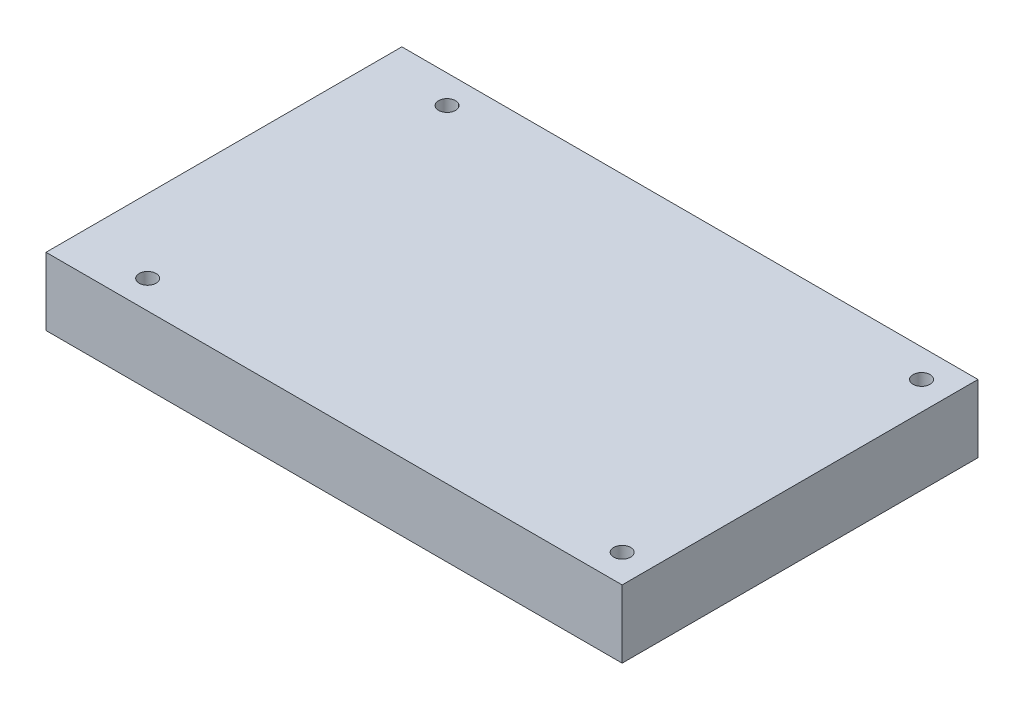
SolidWorks part; units mm, degrees
ref_plane "Front Plane" through (0, 0, 0) normal (0, 0, 1) x (1, 0, 0)
ref_plane "Top Plane" through (0, 0, 0) normal (0, 1, 0) x (1, 0, 0)
ref_plane "Right Plane" through (0, 0, 0) normal (1, 0, 0) x (0, 0, -1)
sketch "Sketch1" plane through (0, 0, 0) normal (0, 1, 0) x (1, 0, 0)
  line L1 (51, -31.5) -> (-51, -31.5)
  line L2 (51, -31.5) -> (51, 31.5)
  line L3 (51, 31.5) -> (-51, 31.5)
  line L4 (-51, -31.5) -> (-51, 31.5)
  line L5 (51, -31.5) -> (-51, 31.5) construction
  line L6 (51, 31.5) -> (-51, -31.5) construction
  point P0 (0, 0)
  dimension "D1" = 102
  dimension "D2" = 63
extrude "Boss-Extrude1" add sketch "Sketch1" along normal blind 12
sketch "Sketch2" plane through (0, 12, 0) normal (0, 1, 0) x (1, 0, 0)
  line L0 (-51, 31.5) -> (-51, -31.5) construction
  line L1 (51, 31.5) -> (-51, 31.5) construction
  circle A0 centre (-38, 26.5) radius 1.5
  circle A1 centre (46, 26.5) radius 1.5
  circle A2 centre (46, -26.5) radius 1.5
  circle A3 centre (-38, -26.5) radius 1.5
  dimension "D1" = 3
  dimension "D2" = 13
  dimension "D3" = 5
  dimension "D4" = 2
  dimension "D6" = 84
  dimension "D7" = 53
  dimension "D5" = 2
extrude "Cut-Extrude1" cut sketch "Sketch2" against normal through all
